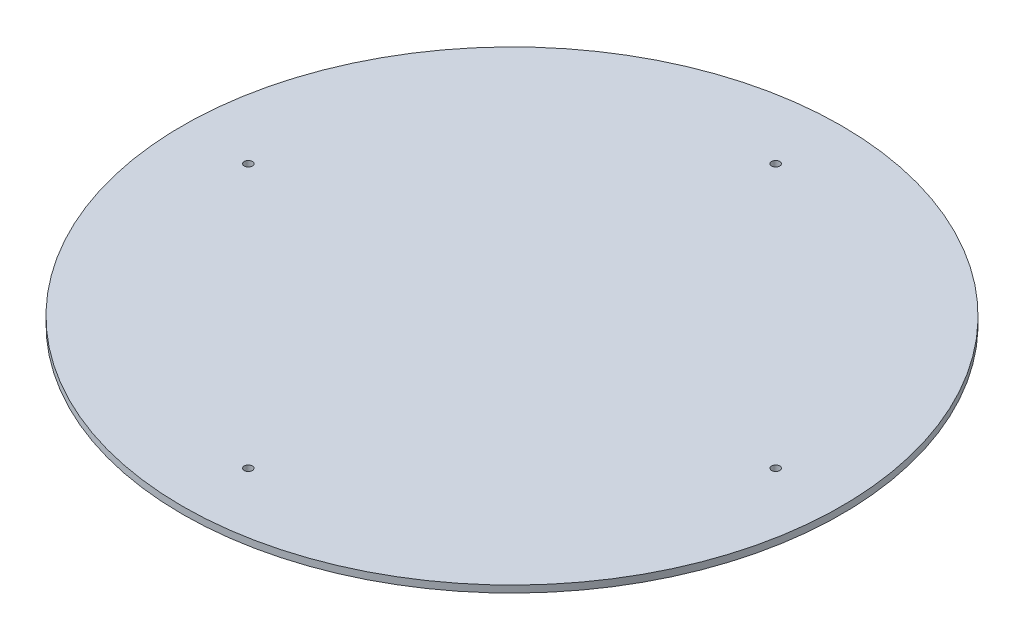
SolidWorks part; units mm, degrees
ref_plane "Front Plane" through (0, 0, 0) normal (0, 0, 1) x (1, 0, 0)
ref_plane "Top Plane" through (0, 0, 0) normal (0, 1, 0) x (1, 0, 0)
ref_plane "Right Plane" through (0, 0, 0) normal (1, 0, 0) x (0, 0, -1)
sketch "Sketch1" plane through (0, 0, 0) normal (0, 1, 0) x (1, 0, 0)
  circle A0 centre (0, 0) radius 285
  dimension "D1" = 570
extrude "Boss-Extrude1" add sketch "Sketch1" along normal blind 6
sketch "Croquis2" plane through (0, 6, 0) normal (0, 1, 0) x (1, 0, 0)
  line L0 (0, 0) -> (0, 58.143) construction
  line L1 (0, 0) -> (228.04, 0) construction
  circle A0 centre (228.04, 0) radius 3.5
  circle A2 centre (0, -228.04) radius 3.5
  circle A3 centre (-228.04, 0) radius 3.5
  circle A4 centre (0, 228.04) radius 3.5
  point P14 (0, 0)
  dimension "D2" = 7
  dimension "D1" = 228.04
  dimension "D3" = 4
extrude "Cortar-Extruir1" cut sketch "Croquis2" against normal through all
